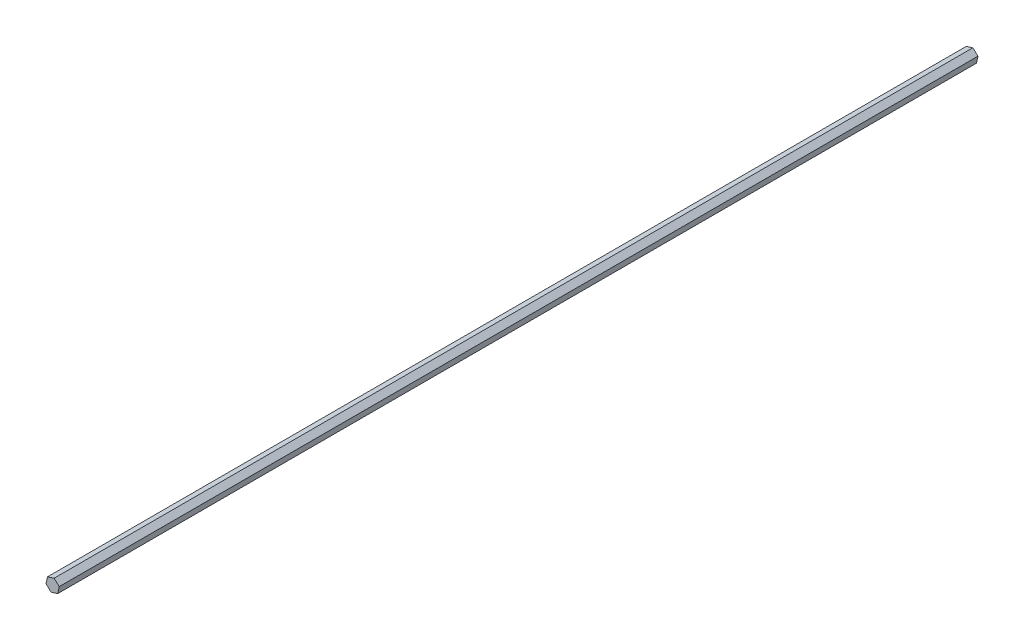
SolidWorks part; units mm, degrees
ref_plane "Front Plane" through (0, 0, 0) normal (0, 0, 1) x (1, 0, 0)
ref_plane "Top Plane" through (0, 0, 0) normal (0, 1, 0) x (1, 0, 0)
ref_plane "Right Plane" through (0, 0, 0) normal (1, 0, 0) x (0, 0, -1)
sketch "Sketch1" plane through (0, 0, 0) normal (0, 0, 1) x (1, 0, 0)
  line L1 (2.1373, -1.9404) -> (2.7491, 0.8807)
  line L2 (2.7491, 0.8807) -> (0.6118, 2.8212)
  line L3 (0.6118, 2.8212) -> (-2.1373, 1.9404)
  line L4 (-2.1373, 1.9404) -> (-2.7491, -0.8807)
  line L5 (-2.7491, -0.8807) -> (-0.6118, -2.8212)
  line L6 (-0.6118, -2.8212) -> (2.1373, -1.9404)
  circle A0 centre (0, 0) radius 2.5 construction
extrude "Boss-Extrude1" add sketch "Sketch1" along normal blind 381
